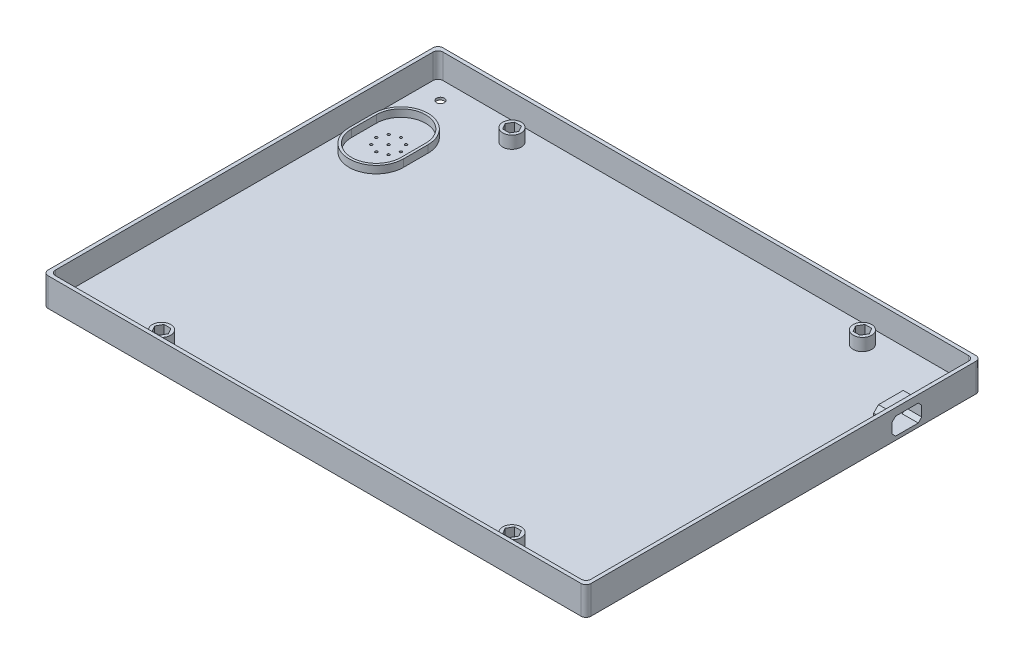
SolidWorks part; units mm, degrees
material "聚脂树脂"
ref_plane "前视基准面" through (0, 0, 0) normal (0, 0, 1) x (1, 0, 0)
ref_plane "上视基准面" through (0, 0, 0) normal (0, 1, 0) x (1, 0, 0)
ref_plane "右视基准面" through (0, 0, 0) normal (1, 0, 0) x (0, 0, -1)
sketch "草图1" plane through (0, 0, 0) normal (0, 1, 0) x (1, 0, 0)
  line L1 (-110, 80) -> (110, 80)
  line L2 (-110, 80) -> (-110, -80)
  line L3 (-110, -80) -> (110, -80)
  line L4 (110, 80) -> (110, -80)
  line L5 (-110, 80) -> (110, -80) construction
  line L6 (-110, -80) -> (110, 80) construction
  point P0 (0, 0)
  dimension "D1" = 160
  dimension "D2" = 220
extrude "凸台-拉伸1" add sketch "草图1" along normal blind 1 and the other way blind 0.5
sketch "草图2" plane through (0, 1, 0) normal (0, 1, 0) x (1, 0, 0)
  line L0 (0, 0) -> (140.9154, 0) construction
  line L1 (0, 0) -> (0, 75.7281) construction
  line L2 (72.3856, 68.6) -> (69.6144, 68.6)
  line L3 (-69.6144, 68.6) -> (-68.2287, 71)
  line L4 (-68.2287, 71) -> (-69.6144, 73.4)
  line L5 (-69.6144, 73.4) -> (-72.3856, 73.4)
  line L6 (-72.3856, 73.4) -> (-73.7713, 71)
  line L7 (-73.7713, 71) -> (-72.3856, 68.6)
  line L8 (-72.3856, 68.6) -> (-69.6144, 68.6)
  line L9 (73.7713, 71) -> (72.3856, 68.6)
  line L10 (72.3856, 73.4) -> (73.7713, 71)
  line L11 (69.6144, 73.4) -> (72.3856, 73.4)
  line L12 (68.2287, 71) -> (69.6144, 73.4)
  line L13 (69.6144, 68.6) -> (68.2287, 71)
  line L14 (69.6144, -68.6) -> (68.2287, -71)
  line L15 (68.2287, -71) -> (69.6144, -73.4)
  line L16 (69.6144, -73.4) -> (72.3856, -73.4)
  line L17 (72.3856, -73.4) -> (73.7713, -71)
  line L18 (73.7713, -71) -> (72.3856, -68.6)
  line L19 (-72.3856, -68.6) -> (-69.6144, -68.6)
  line L20 (-73.7713, -71) -> (-72.3856, -68.6)
  line L21 (-72.3856, -73.4) -> (-73.7713, -71)
  line L22 (-69.6144, -73.4) -> (-72.3856, -73.4)
  line L23 (-68.2287, -71) -> (-69.6144, -73.4)
  line L24 (-69.6144, -68.6) -> (-68.2287, -71)
  line L25 (72.3856, -68.6) -> (69.6144, -68.6)
  circle A0 centre (-71, 71) radius 3.75
  circle A1 centre (-71, 71) radius 2.4 construction
  circle A2 centre (71, 71) radius 2.4 construction
  circle A3 centre (71, 71) radius 3.75
  circle A4 centre (71, -71) radius 2.4 construction
  circle A5 centre (-71, -71) radius 2.4 construction
  circle A6 centre (71, -71) radius 3.75
  circle A7 centre (-71, -71) radius 3.75
  dimension "D2" = 7.5
  dimension "D1" = 4.8
  dimension "D3" = 71
  dimension "D4" = 71
extrude "凸台-拉伸2" add sketch "草图2" along normal blind 5
sketch "草图3" plane through (0, -0.5, 0) normal (0, -1, 0) x (1, 0, 0)
  line L0 (0, 0) -> (23.7598, 0) construction
  line L2 (0, 0) -> (0, -118.758) construction
  circle A0 centre (-100, -71) radius 1.6
  circle A1 centre (100, -71) radius 1.6
  circle A2 centre (100, 71) radius 1.6
  circle A3 centre (-100, 71) radius 1.6
  dimension "D1" = 3.2
  dimension "D2" = 71
  dimension "D3" = 100
extrude "切除-拉伸5" cut sketch "草图3" against normal up to next and the other way through all
ref_plane "基准面1" through (0, 0, 0) normal (0, 1, 0) x (1, 0, 0)
sketch "草图4" plane through (0, 0, 0) normal (0, 1, 0) x (1, 0, 0)
  line L0 (0, 0) -> (-86.2978, 0) construction
  line L1 (0, 0) -> (0, 99.8527) construction
  circle A0 centre (-100, 71) radius 3
  circle A1 centre (100, 71) radius 3
  circle A2 centre (100, -71) radius 3
  circle A3 centre (-100, -71) radius 3
  dimension "D1" = 6
extrude "切除-拉伸7" cut sketch "草图4" along normal blind 0.5 from offset 0.5 offset against normal yes
sketch "草图5" plane through (0, 1, 0) normal (0, 1, 0) x (1, 0, 0)
  line L14 (110, -80) -> (110, 80)
  line L15 (110, 80) -> (-110, 80)
  line L16 (-110, 80) -> (-110, -80)
  line L17 (-110, -80) -> (110, -80)
  line L36 (108.5, -78.5) -> (108.5, 78.5)
  line L37 (108.5, 78.5) -> (-108.5, 78.5)
  line L38 (-108.5, 78.5) -> (-108.5, -78.5)
  line L39 (-108.5, -78.5) -> (108.5, -78.5)
  dimension "D1" = 1.5
extrude "凸台-拉伸3" add sketch "草图5" along normal blind 10
fillet "圆角1" radius 2 1 edges at (-110, 5.25, -80)
fillet "圆角2" radius 2 1 edges at (-108.5, 6, -78.5)
fillet "圆角3" radius 2 6 edges at (-108.5, 6, 78.5) (-110, 5.25, 80) (108.5, 6, 78.5) (110, 5.25, 80) (108.5, 6, -78.5) (110, 5.25, -80)
sketch "草图7" plane through (110, 0, 0) normal (1, 0, 0) x (0, 0, -1)
  line L0 (-78, -0.5) -> (78, -0.5) construction
  line L1 (45.436, 8) -> (54.6075, 8)
  line L2 (44.0217, 6.5858) -> (44.0217, 2.4142)
  line L3 (45.436, 1) -> (54.6075, 1)
  line L4 (56.0217, 6.5858) -> (56.0217, 2.4142)
  line L5 (44.6647, 7.2288) -> (55.2175, 1.61) construction
  line L6 (44.9147, 1.5212) -> (55.2563, 7.3512) construction
  line L7 (45.436, 8) -> (44.0217, 6.5858)
  line L8 (50.0217, 4.388) -> (50.0217, 11.8699) construction
  line L9 (50, 4.5) -> (41.7258, 4.5) construction
  line L10 (54.6075, 8) -> (56.0217, 6.5858)
  line L11 (54.6075, 1) -> (56.0217, 2.4142)
  line L12 (45.436, 1) -> (44.0217, 2.4142)
  point P0 (50, 4.388)
  dimension "D1" = 50
  dimension "D2" = 7
  dimension "D3" = 12
  dimension "D4" = 1.5
  dimension "D5" = 135
  dimension "D6" = 2
extrude "切除-拉伸8" cut sketch "草图7" against normal up to next and the other way through all
sketch "草图8" plane through (108.5, 0, 0) normal (-1, 0, 0) x (0, 0, 1)
  line L0 (-43.0217, 2.4142) -> (-43.0217, 7)
  line L1 (-43.0217, 7) -> (-45.0217, 9)
  line L2 (-45.0217, 9) -> (-55.0217, 9)
  line L3 (-55.0217, 9) -> (-57.0217, 7)
  line L4 (-57.0217, 7) -> (-57.0217, 2.4142)
  line L5 (-57.0217, 2.4142) -> (-55.6075, 1)
  line L6 (-54.6075, 1) -> (-76.5, 1) construction
  line L7 (-43.0217, 2.4142) -> (-44.436, 1)
  line L8 (-44.0217, 2.4142) -> (-44.0217, 6.5858)
  line L9 (-44.0217, 6.5858) -> (-45.436, 8)
  line L10 (-45.436, 8) -> (-54.6075, 8)
  line L11 (-54.6075, 8) -> (-56.0217, 6.5858)
  line L12 (-56.0217, 6.5858) -> (-56.0217, 2.4142)
  line L13 (-56.0217, 2.4142) -> (-54.6075, 1)
  line L14 (-54.6075, 1) -> (-45.436, 1)
  line L15 (-45.436, 1) -> (-44.0217, 2.4142)
  line L16 (-44.0217, 2.4142) -> (-44.0217, 6.5858)
  line L17 (-44.0217, 6.5858) -> (-45.436, 8)
  line L18 (-45.436, 8) -> (-54.6075, 8)
  line L19 (-54.6075, 8) -> (-56.0217, 6.5858)
  line L20 (-56.0217, 6.5858) -> (-56.0217, 2.4142)
  line L21 (-56.0217, 2.4142) -> (-54.6075, 1)
  line L22 (-54.6075, 1) -> (-45.436, 1)
  line L23 (-45.436, 1) -> (-44.0217, 2.4142)
  line L24 (76.5, 1) -> (-45.436, 1) construction
  line L25 (-55.6075, 1) -> (-44.436, 1)
  line M11 (-44.0217, 6.5858) -> (-44.0217, 2.4142)
  line M12 (-44.0217, 2.4142) -> (-45.436, 1)
  line M13 (-45.436, 1) -> (76.5, 1)
  line M17 (-76.5, 1) -> (-54.6075, 1)
  line M18 (-54.6075, 1) -> (-56.0217, 2.4142)
  line M19 (-56.0217, 2.4142) -> (-56.0217, 6.5858)
  line M20 (-56.0217, 6.5858) -> (-54.6075, 8)
  line M21 (-54.6075, 8) -> (-45.436, 8)
  line M22 (-45.436, 8) -> (-44.0217, 6.5858)
  dimension "D1" = 0
  dimension "D2" = 1
extrude "凸台-拉伸4" add sketch "草图8" along normal blind 5 contours L7 L0 L1 L2 L3 L4 L5 M17 M18 M19 M20 M21 M22 M11 M12 M13
sketch "草图9" plane through (0, 1, 0) normal (0, 1, 0) x (1, 0, 0)
  line L0 (-95, 50) -> (-95, 40) construction
  line L1 (-85, 50) -> (-85, 40)
  line L2 (-105, 50) -> (-105, 40)
  line L3 (-110, 78) -> (-110, -78) construction
  line L4 (108, 80) -> (-108, 80) construction
  line L5 (-84, 50) -> (-84, 40)
  line L6 (-106, 50) -> (-106, 40)
  arc A0 (-85, 50) -> (-105, 50) centre (-95, 50) ccw
  arc A1 (-105, 40) -> (-85, 40) centre (-95, 40) ccw
  arc A2 (-106, 40) -> (-84, 40) centre (-95, 40) ccw
  arc A3 (-84, 50) -> (-106, 50) centre (-95, 50) ccw
  point P2 (-95, 45)
  dimension "D1" = 10
  dimension "D2" = 10
  dimension "D3" = 15
  dimension "D4" = 35
  dimension "D5" = 1
extrude "凸台-拉伸5" add sketch "草图9" along normal blind 3
sketch "草图10" plane through (0, 1, 0) normal (0, 1, 0) x (1, 0, 0)
  line L0 (-110, 78) -> (-110, -78) construction
  line L1 (108, 80) -> (-108, 80) construction
  circle A0 centre (-95, 45) radius 0.5
  circle A5 centre (-100, 45) radius 0.5
  circle A6 centre (-98.5355, 48.5355) radius 0.5
  circle A7 centre (-95, 50) radius 0.5
  circle A8 centre (-91.4645, 48.5355) radius 0.5
  circle A9 centre (-90, 45) radius 0.5
  circle A10 centre (-91.4645, 41.4645) radius 0.5
  circle A11 centre (-95, 40) radius 0.5
  circle A12 centre (-98.5355, 41.4645) radius 0.5
  point P25 (-95, 45)
  dimension "D3" = 1
  dimension "D1" = 15
  dimension "D2" = 35
  dimension "D4" = 2
  dimension "D5" = 8
extrude "切除-拉伸9" cut sketch "草图10" against normal up to next
